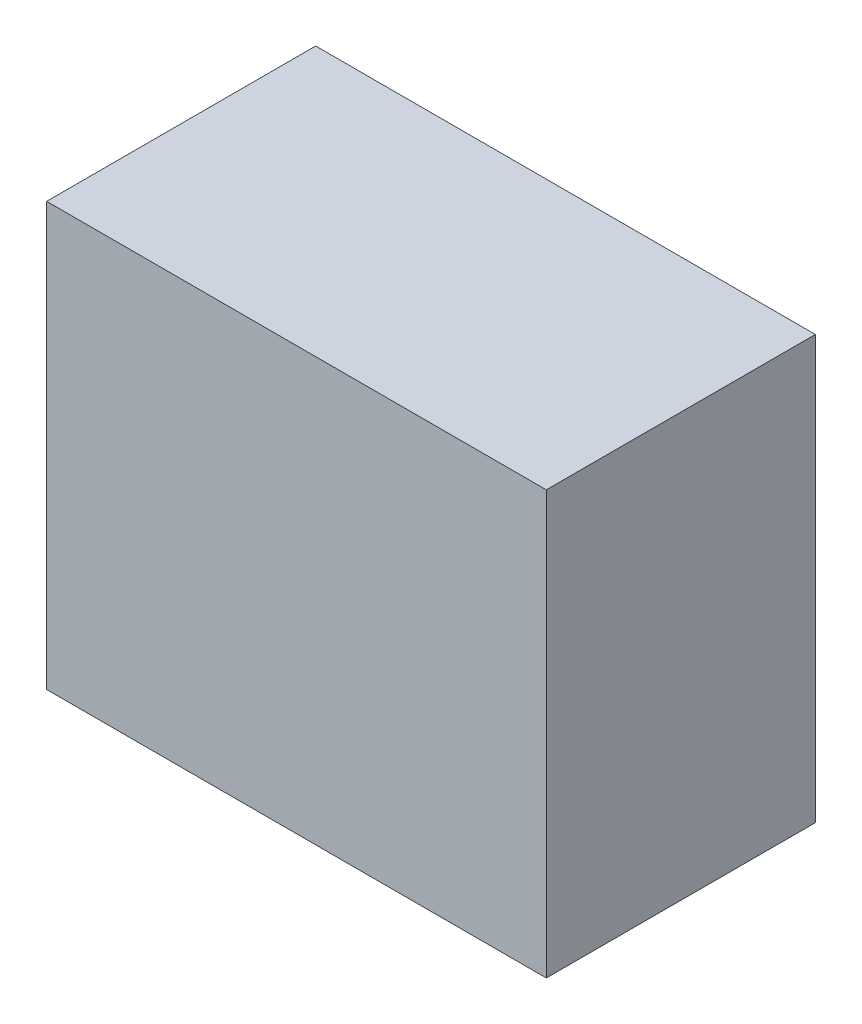
SolidWorks part; units mm, degrees
ref_plane "Front Plane" through (0, 0, 0) normal (0, 0, 1) x (1, 0, 0)
ref_plane "Top Plane" through (0, 0, 0) normal (0, 1, 0) x (1, 0, 0)
ref_plane "Right Plane" through (0, 0, 0) normal (1, 0, 0) x (0, 0, -1)
sketch "Sketch1" plane through (0, 0, 0) normal (0, 0, 1) x (1, 0, 0)
  line L1 (-32.5, -27.5) -> (32.5, -27.5)
  line L2 (-32.5, -27.5) -> (-32.5, 27.5)
  line L3 (-32.5, 27.5) -> (32.5, 27.5)
  line L4 (32.5, -27.5) -> (32.5, 27.5)
  line L5 (-32.5, -27.5) -> (32.5, 27.5) construction
  line L6 (-32.5, 27.5) -> (32.5, -27.5) construction
  point P0 (0, 0)
  dimension "D1" = 65
  dimension "D2" = 55
extrude "Boss-Extrude1" add sketch "Sketch1" along normal blind 35
sketch "Sketch2" plane through (-32.5, 0, 0) normal (-1, 0, 0) x (0, 0, 1)
  line L0 (0, 27.5) -> (0, -27.5) construction
  line L1 (33, -25.5) -> (2, -25.5)
  line L2 (33, -25.5) -> (33, 25.5)
  line L3 (33, 25.5) -> (2, 25.5)
  line L4 (2, -25.5) -> (2, 25.5)
  line L5 (35, 27.5) -> (35, -27.5) construction
  line L6 (35, -27.5) -> (0, -27.5) construction
  line L7 (35, 27.5) -> (0, 27.5) construction
  dimension "D1" = 2
  dimension "D2" = 2
  dimension "D3" = 2
  dimension "D4" = 2
extrude "Cut-Extrude1" cut sketch "Sketch2" against normal blind 60
